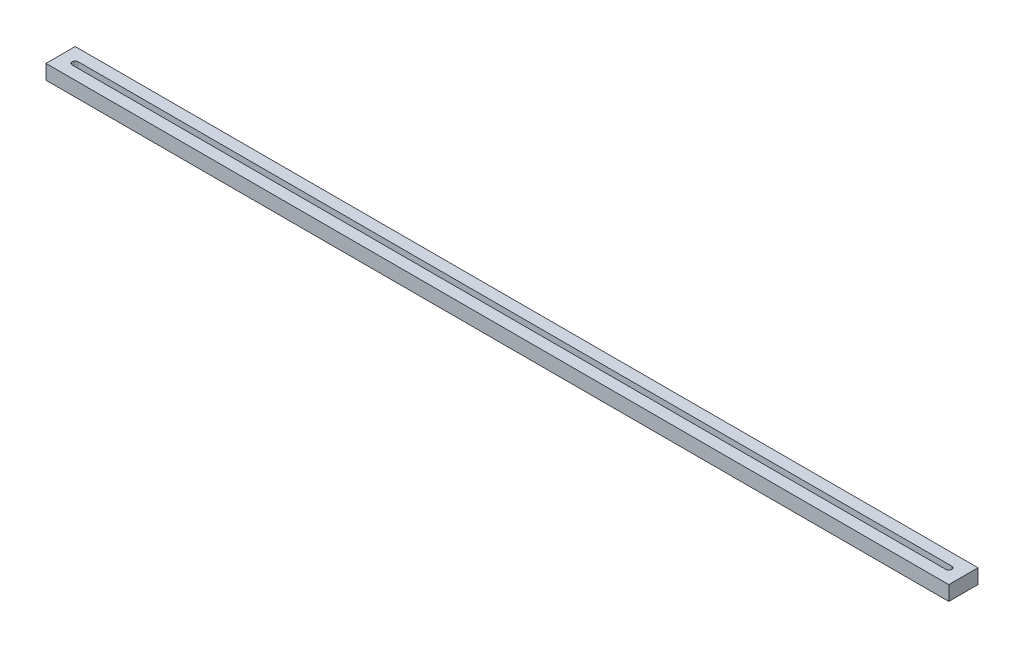
SolidWorks part; units mm, degrees
ref_plane "Front Plane" through (0, 0, 0) normal (0, 0, 1) x (1, 0, 0)
ref_plane "Top Plane" through (0, 0, 0) normal (0, 1, 0) x (1, 0, 0)
ref_plane "Right Plane" through (0, 0, 0) normal (1, 0, 0) x (0, 0, -1)
sketch "Sketch1" plane through (0, 0, 0) normal (0, 1, 0) x (1, 0, 0)
  line L0 (10.4755, 18.1185) -> (319.4755, 18.1185)
  line L1 (10.4755, 8.1185) -> (319.4755, 8.1185)
  line L2 (10.4755, 18.1185) -> (10.4755, 8.1185)
  line L3 (319.4755, 18.1185) -> (319.4755, 8.1185)
  line L6 (15.4755, 13.1185) -> (314.4755, 13.1185) construction
  line L7 (15.4755, 14.1185) -> (314.4755, 14.1185)
  line L8 (15.4755, 12.1185) -> (314.4755, 12.1185)
  arc A0 (15.4755, 14.1185) -> (15.4755, 12.1185) centre (15.4755, 13.1185) ccw
  arc A1 (314.4755, 12.1185) -> (314.4755, 14.1185) centre (314.4755, 13.1185) ccw
  point P10 (164.9755, 13.1185)
  dimension "D1" = 10
extrude "Boss-Extrude1" add sketch "Sketch1" along normal blind 5
